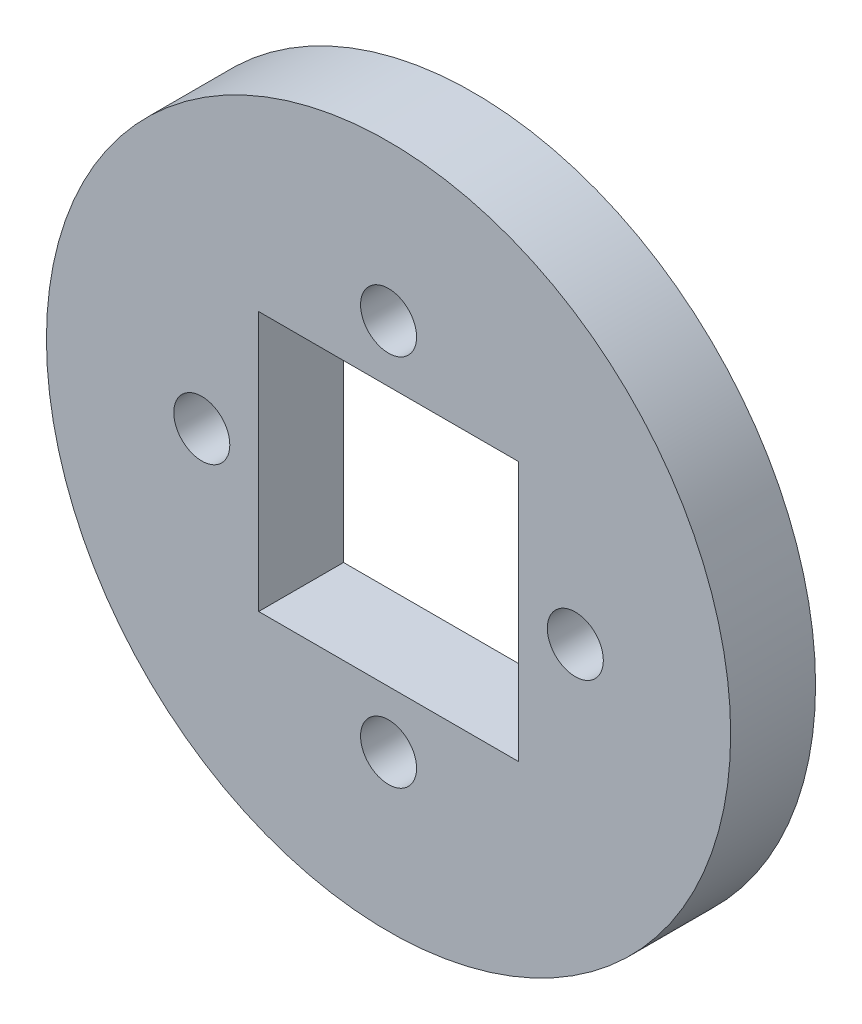
SolidWorks part; units mm, degrees
ref_plane "Front Plane" through (0, 0, 0) normal (0, 0, 1) x (1, 0, 0)
ref_plane "Top Plane" through (0, 0, 0) normal (0, 1, 0) x (1, 0, 0)
ref_plane "Right Plane" through (0, 0, 0) normal (1, 0, 0) x (0, 0, -1)
sketch "Sketch1" plane through (0, 0, 0) normal (0, 0, 1) x (1, 0, 0)
  line L0 (-15.3, 15.3) -> (-15.3, -15.3) construction
  line L1 (-15.3, -15.3) -> (15.3, -15.3) construction
  line L2 (15.3, -15.3) -> (15.3, 15.3) construction
  line L3 (15.3, 15.3) -> (-15.3, 15.3) construction
  line L4 (-15.3, 15.3) -> (-15.3, -15.3)
  line L5 (-15.3, -15.3) -> (15.3, -15.3)
  line L6 (15.3, -15.3) -> (15.3, 15.3)
  line L7 (15.3, 15.3) -> (-15.3, 15.3)
  arc A0 (-40.3, -0.0339) -> (4.25, 40.0753) centre (0, 0) ccw construction
  arc A1 (-40.3, -0.0339) -> (4.25, 40.0753) centre (0, 0) ccw construction
  circle A2 centre (0, 0) radius 40.3
  circle A3 centre (0, 22) radius 1.65
  circle A4 centre (22, 0) radius 1.65
  circle A5 centre (0, -22) radius 1.65
  circle A6 centre (-22, 0) radius 1.65
  dimension "D1" = 3.3
extrude "Boss-Extrude1" add sketch "Sketch1" along normal blind 10
sketch "Sketch2" plane through (0, 0, 10) normal (0, 0, 1) x (1, 0, 0)
  circle A0 centre (22, 0) radius 3.3
  circle A1 centre (0, 22) radius 3.3
  circle A2 centre (-22, 0) radius 3.3
  circle A3 centre (0, -22) radius 3.3
  dimension "D1" = 6.6
extrude "Cut-Extrude1" cut sketch "Sketch2" against normal blind 6
